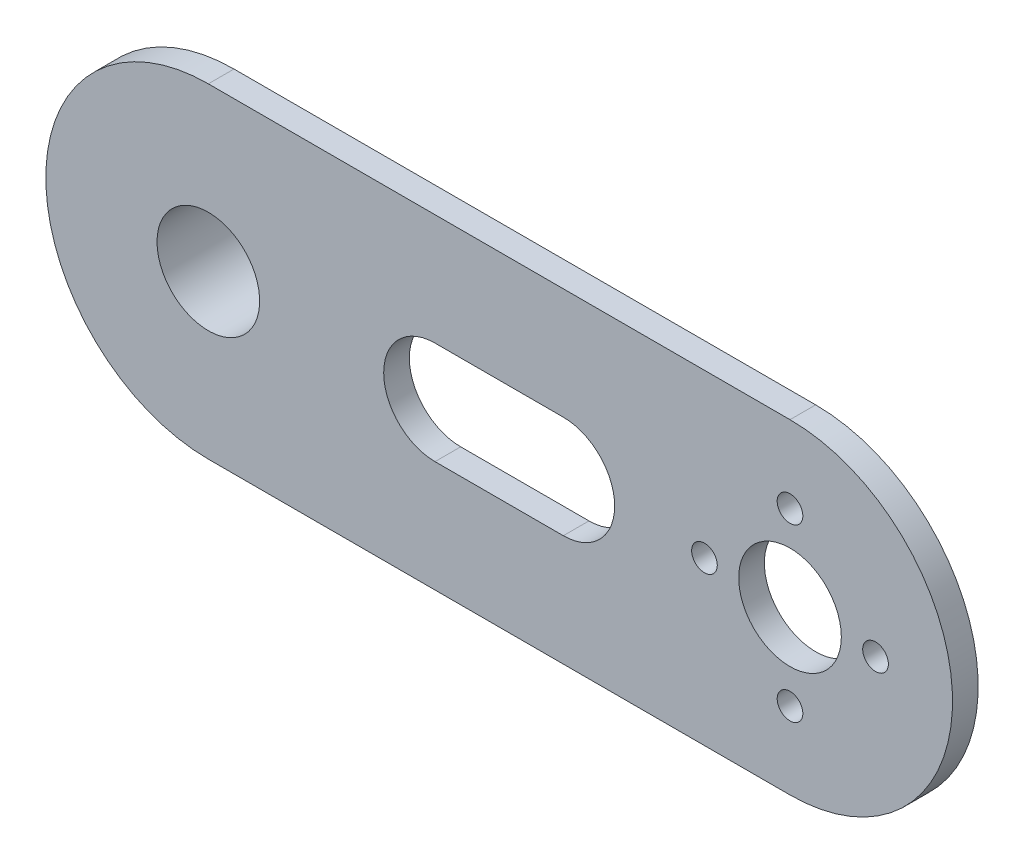
SolidWorks part; units mm, degrees
ref_plane "前视基准面" through (0, 0, 0) normal (0, 0, 1) x (1, 0, 0)
ref_plane "上视基准面" through (0, 0, 0) normal (0, 1, 0) x (1, 0, 0)
ref_plane "右视基准面" through (0, 0, 0) normal (1, 0, 0) x (0, 0, -1)
other "Configuration Table"
sketch "草图1" plane through (0, 0, 0) normal (0, 0, 1) x (1, 0, 0)
  circle A0 centre (0, 0) radius 9.985
  dimension "D1" = 19.97
extrude "凸台-拉伸1" add sketch "草图1" along normal blind 4
sketch "草图2" plane through (0, 0, 4) normal (0, 0, 1) x (1, 0, 0)
  circle A0 centre (0, 0) radius 11.5
  dimension "D1" = 23
extrude "凸台-拉伸2" add sketch "草图2" along normal blind 2
sketch "草图3" plane through (0, 0, 6) normal (0, 0, 1) x (1, 0, 0)
  circle A0 centre (0, 0) radius 19
  circle A1 centre (0, 15) radius 1.5 construction
  circle A2 centre (12.9904, 7.5) radius 1.5 construction
  circle A3 centre (12.9904, -7.5) radius 1.5 construction
  circle A4 centre (0, -15) radius 1.5 construction
  circle A5 centre (-12.9904, -7.5) radius 1.5 construction
  circle A6 centre (-12.9904, 7.5) radius 1.5 construction
  point P17 (0, 0)
  dimension "D1" = 38
  dimension "D2" = 3
  dimension "D3" = 15
  dimension "D4" = 6
extrude "凸台-拉伸3" add sketch "草图3" along normal blind 3
sketch "草图4" plane through (0, 0, 0) normal (0, 0, -1) x (-1, 0, 0)
  circle A0 centre (0, 0) radius 6
  dimension "D1" = 12
extrude "切除-拉伸1" cut sketch "草图4" against normal through all
sketch "草图5" plane through (0, 0, 9) normal (0, 0, 1) x (1, 0, 0)
  line L0 (0, 19) -> (68, 19)
  line L1 (68, -19) -> (0, -19)
  circle A1 centre (0, 0) radius 6
  circle A2 centre (0, 0) radius 6
  circle A3 centre (0, 0) radius 6
  circle A5 centre (0, 0) radius 6
  circle A7 centre (0, 0) radius 6
  circle A9 centre (0, 0) radius 6
  circle A11 centre (0, 0) radius 6
  circle A13 centre (0, 0) radius 6
  circle A15 centre (0, 0) radius 19
  circle A16 centre (0, 0) radius 19
  circle A17 centre (68, 0) radius 6
  circle A24 centre (68, 0) radius 19
  circle A25 centre (68, 10) radius 1.5
  circle A32 centre (78, 0) radius 1.5
  circle A33 centre (68, -10) radius 1.5
  circle A34 centre (58, 0) radius 1.5
  circle A36 centre (0, 0) radius 6
  circle A37 centre (0, 0) radius 6
  circle A38 centre (0, 0) radius 6
  circle A39 centre (0, 0) radius 6
  circle A40 centre (0, 0) radius 6
  circle A41 centre (0, 0) radius 6
  point P37 (68, 0)
  dimension "D11" = 3
  dimension "D10" = 68
  dimension "D12" = 10
  dimension "D1" = 0
  dimension "D2" = 0
  dimension "D3" = 0
  dimension "D4" = 0
  dimension "D5" = 0
  dimension "D6" = 0
  dimension "D7" = 0
  dimension "D8" = 0
  dimension "D9" = 2
  dimension "D13" = 4
extrude "凸台-拉伸4" add sketch "草图5" against normal blind 3
sketch "草图6" plane through (0, 0, 9) normal (0, 0, 1) x (1, 0, 0)
  line L0 (0, 0) -> (68, 0) construction
  line L1 (26.5, 0) -> (41.5, 0) construction
  line L2 (26.5, 6) -> (41.5, 6)
  line L3 (26.5, -6) -> (41.5, -6)
  circle A0 centre (68, 0) radius 6 construction
  circle A1 centre (68, 0) radius 6
  arc A2 (26.5, 6) -> (26.5, -6) centre (26.5, 0) ccw
  arc A3 (41.5, -6) -> (41.5, 6) centre (41.5, 0) ccw
  point P7 (34, 0)
  dimension "D1" = 6
  dimension "D2" = 15
extrude "切除-拉伸2" cut sketch "草图6" against normal through all
